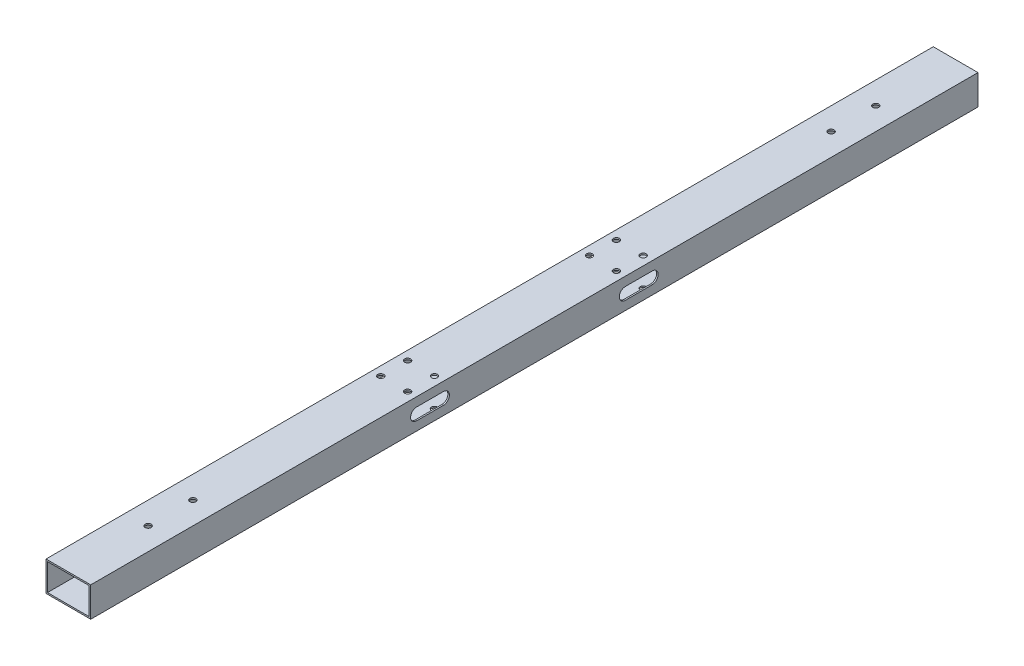
SolidWorks part; units mm, degrees
material "6061 合金"
ref_plane "前视基准面" through (0, 0, 0) normal (0, 0, 1) x (1, 0, 0)
ref_plane "上视基准面" through (0, 0, 0) normal (0, 1, 0) x (1, 0, 0)
ref_plane "右视基准面" through (0, 0, 0) normal (1, 0, 0) x (0, 0, -1)
sketch "草图1" plane through (0, 0, 0) normal (0, 0, 1) x (1, 0, 0)
  line L0 (-14, -9) -> (-14, 9)
  line L1 (-15, -10) -> (15, -10)
  line L2 (-15, -10) -> (-15, 10)
  line L3 (-15, 10) -> (15, 10)
  line L4 (15, -10) -> (15, 10)
  line L5 (0, 10) -> (0, -10) construction
  line L6 (-15, 0) -> (15, 0) construction
  line L7 (-14, 9) -> (14, 9)
  line L8 (14, -9) -> (14, 9)
  line L9 (-14, -9) -> (14, -9)
  point P0 (0, 0)
  dimension "D1" = 20
  dimension "D2" = 30
  dimension "D3" = 1
extrude "凸台-拉伸1" add sketch "草图1" along normal mid plane 595
sketch "草图2" plane through (0, 10, 0) normal (0, 1, 0) x (1, 0, 0)
  line L0 (165, 85) -> (-425, 85) construction
  line L1 (165, 55) -> (-425, 55) construction
  line L2 (15, 85) -> (-15, 85) construction
  line L3 (15, 55) -> (-15, 55) construction
  line L4 (-15, -297.5) -> (-15, 297.5) construction
  line L5 (15, -297.5) -> (15, 297.5) construction
  line L6 (-15, 55) -> (-15, 85) construction
  line L7 (15, 55) -> (15, 85) construction
  line L8 (-15, 85) -> (15, 55) construction
  line L10 (-9, 61) -> (9, 61) construction
  line L11 (-9, 61) -> (-9, 79) construction
  line L12 (-9, 79) -> (9, 79) construction
  line L13 (9, 61) -> (9, 79) construction
  line L14 (0, 79) -> (0, 61) construction
  line L15 (-9, 70) -> (9, 70) construction
  circle A0 centre (9, 79) radius 2
  circle A1 centre (-9, 79) radius 2
  circle A2 centre (-9, 61) radius 2
  circle A3 centre (9, 61) radius 2
  point P12 (0, 70)
  dimension "D2" = 4
  dimension "D1" = 18
extrude "切除-拉伸1" cut sketch "草图2" against normal blind 70
mirror "镜向1" about plane through (0, 0, 0) normal (0, 0, 1) of "切除-拉伸1"
sketch "草图4" plane through (15, 0, 0) normal (1, 0, 0) x (0, 0, -1)
  line L0 (-59, 10) -> (-63, 10) construction
  line L1 (-77, 10) -> (-81, 10) construction
  line L2 (-59, 10) -> (-63, 10) construction
  line L3 (-77, 10) -> (-81, 10) construction
  line L4 (-61, 10) -> (-61, -10) construction
  line L5 (-297.5, -10) -> (297.5, -10) construction
  line L6 (-61, -10) -> (-79, 10) construction
  line L7 (-79, 0) -> (-61, 0) construction
  line L8 (-79, 4) -> (-61, 4)
  line L9 (-79, -4) -> (-61, -4)
  arc A0 (-79, 4) -> (-79, -4) centre (-79, 0) ccw
  arc A1 (-61, -4) -> (-61, 4) centre (-61, 0) ccw
  point P11 (-70, 0)
  dimension "D1" = 4
extrude "切除-拉伸2" cut sketch "草图4" against normal blind 65
mirror "镜向2" about plane through (0, 0, 0) normal (0, 0, 1) of "切除-拉伸2"
sketch "草图5" plane through (0, -10, 0) normal (0, -1, 0) x (1, 0, 0)
  circle A0 centre (0, -244) radius 2 construction
  circle A1 centre (0, -214) radius 2 construction
  circle A2 centre (0, -244) radius 2
  circle A3 centre (0, -214) radius 2
extrude "切除-拉伸3" cut sketch "草图5" against normal mid plane 70
mirror "镜向3" about plane through (0, 0, 0) normal (0, 0, 1) of "切除-拉伸3"
